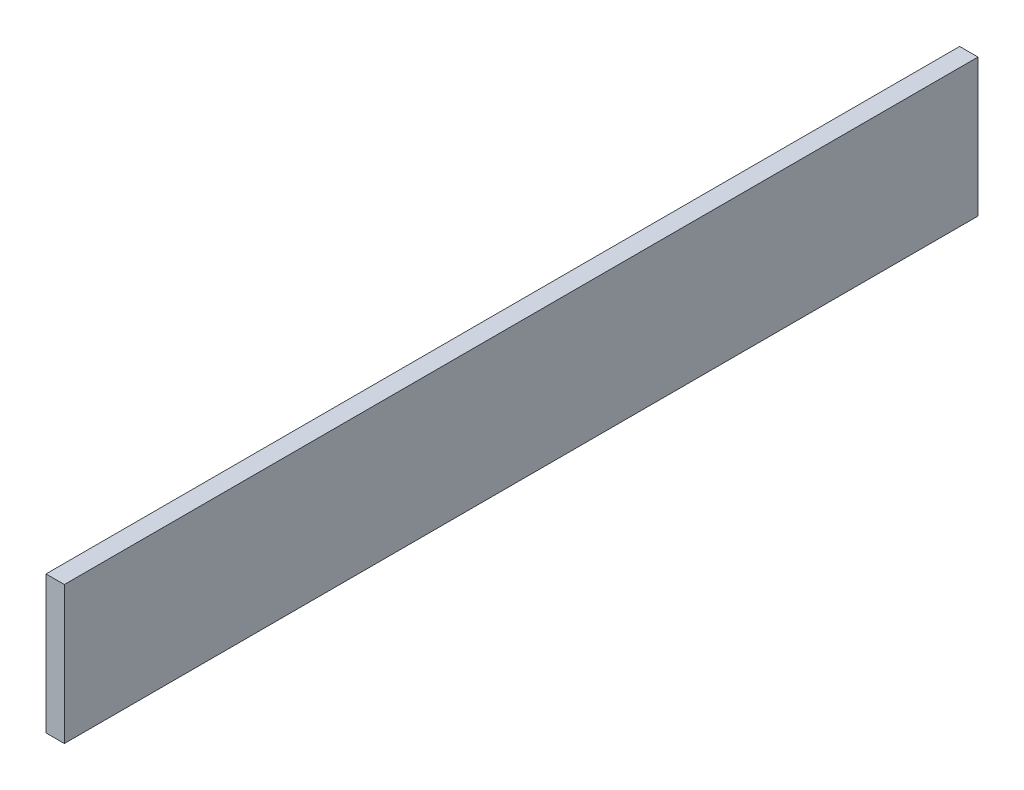
SolidWorks part; units mm, degrees
material "Plain Carbon Steel"
ref_plane "Front Plane" through (0, 0, 0) normal (0, 0, 1) x (1, 0, 0)
ref_plane "Top Plane" through (0, 0, 0) normal (0, 1, 0) x (1, 0, 0)
ref_plane "Right Plane" through (0, 0, 0) normal (1, 0, 0) x (0, 0, -1)
sketch "Sketch1" plane through (0, 0, 0) normal (0, 0, 1) x (1, 0, 0)
  line L1 (-4, -30) -> (4, -30)
  line L2 (-4, -30) -> (-4, 30)
  line L3 (-4, 30) -> (4, 30)
  line L4 (4, -30) -> (4, 30)
  line L5 (-4, -30) -> (4, 30) construction
  line L6 (-4, 30) -> (4, -30) construction
  point P0 (0, 0)
  dimension "D1" = 60
  dimension "D2" = 8
extrude "Boss-Extrude1" add sketch "Sketch1" along normal mid plane 398
